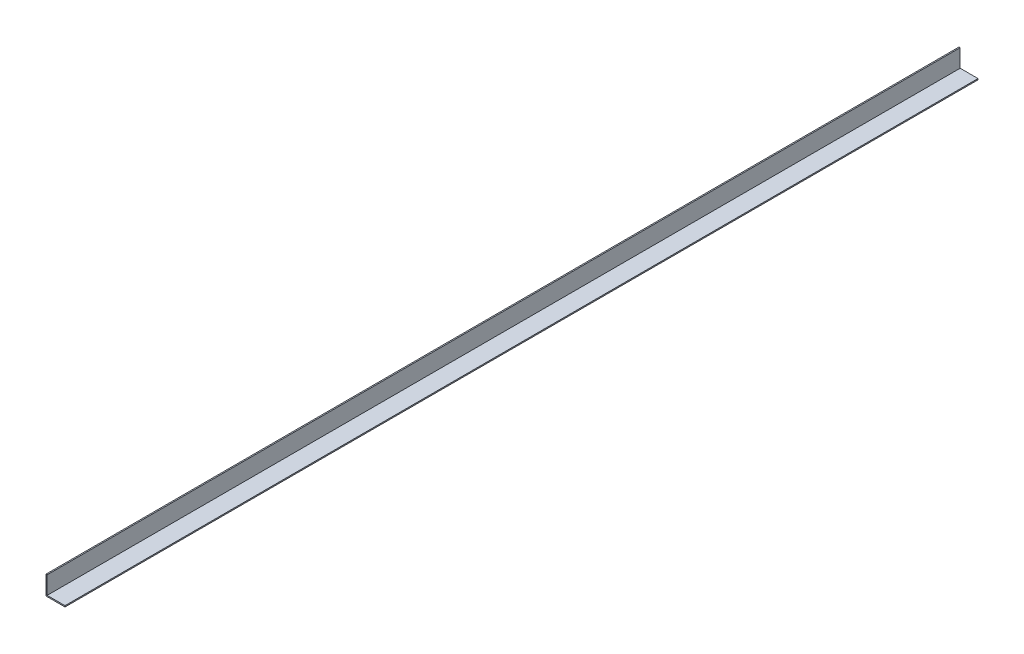
SolidWorks part; units mm, degrees
material "ASTM A36 Acero"
ref_plane "Alzado" through (0, 0, 0) normal (0, 0, 1) x (1, 0, 0)
ref_plane "Planta" through (0, 0, 0) normal (0, 1, 0) x (1, 0, 0)
ref_plane "Vista lateral" through (0, 0, 0) normal (1, 0, 0) x (0, 0, -1)
sketch "Croquis1" plane through (0, 0, 0) normal (0, 0, 1) x (1, 0, 0)
  line L0 (0, 127) -> (0, 0)
  line L1 (0, 0) -> (127, 0)
  line L2 (127, 0) -> (127, 7.94)
  line L3 (127, 7.94) -> (7.94, 7.94)
  line L4 (7.94, 7.94) -> (7.94, 127)
  line L5 (7.94, 127) -> (0, 127)
  dimension "D1" = 7.94
  dimension "D2" = 127
extrude "Saliente-Extruir1" add sketch "Croquis1" against normal blind 6100
